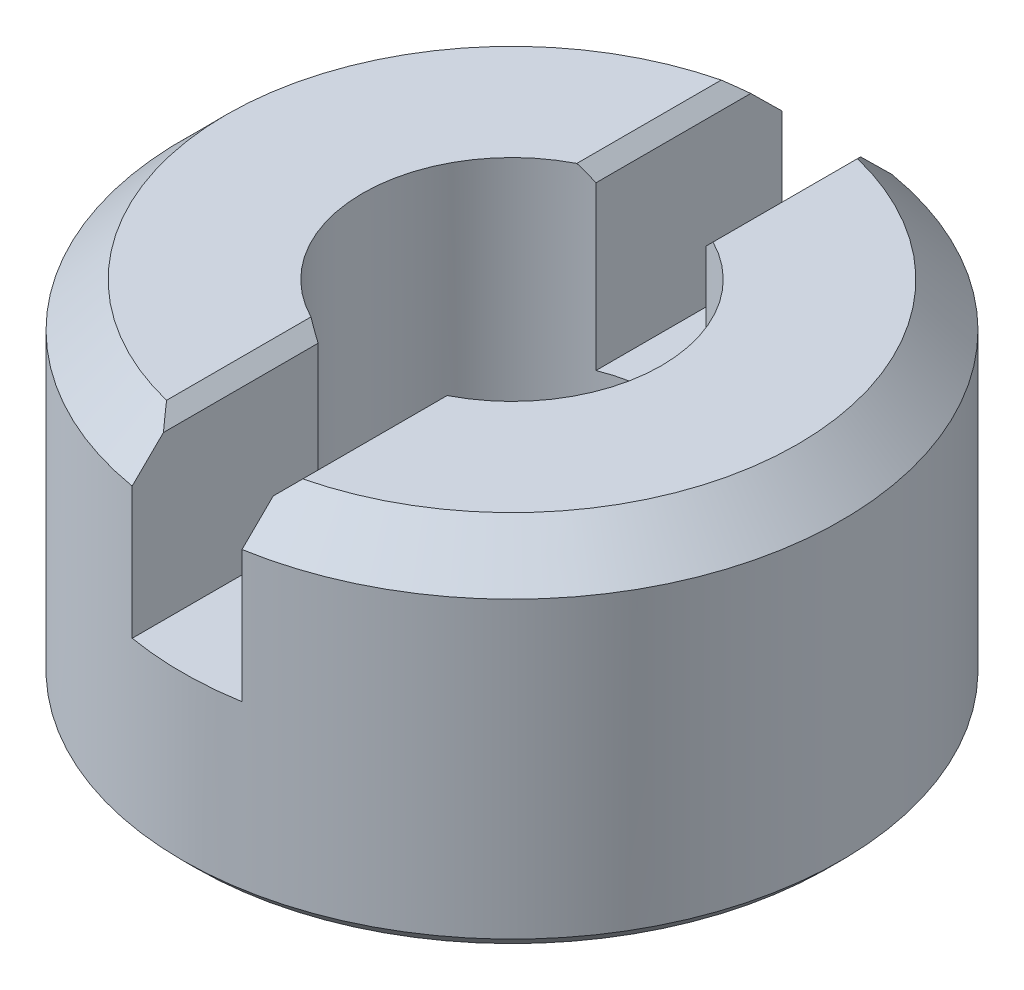
SolidWorks part; units mm, degrees
ref_plane "Přední rovina" through (0, 0, 0) normal (0, 0, 1) x (1, 0, 0)
ref_plane "Vrchní rovina" through (0, 0, 0) normal (0, 1, 0) x (1, 0, 0)
ref_plane "Pravá rovina" through (0, 0, 0) normal (1, 0, 0) x (0, 0, -1)
sketch "Skica1" plane through (0, 0, 0) normal (0, 1, 0) x (1, 0, 0)
  circle A0 centre (0, 0) radius 1.5
  dimension "D1" = 3
extrude "Vysunout1" add sketch "Skica1" along normal blind 1.6
sketch "Skica2" plane through (0, 1.6, 0) normal (0, 1, 0) x (-1, 0, 0)
  line L0 (0, 0) -> (0, 1.5) construction
  line L1 (-0.25, -1.5) -> (0.25, -1.5)
  line L2 (-0.25, -1.5) -> (-0.25, 1.5)
  line L3 (-0.25, 1.5) -> (0.25, 1.5)
  line L4 (0.25, -1.5) -> (0.25, 1.5)
  circle A0 centre (0, 0) radius 1.5 construction
  dimension "n" = 0.5
extrude "Odebrat vysunutím2" cut sketch "Skica2" against normal blind 0.8
chamfer "Zkosit1" distance 0.2 angle 45 2 edges at (1.5, 1.6, 0) (-1.5, 1.6, 0)
chamfer "Zkosit3" distance 0.06 angle 45 5 edges at (0, 0, 1.5) (-0.25, 1.6, 0) (0.25, 1.6, 0)
sketch "Skica3" plane through (0, 0, 0) normal (0, -1, 0) x (1, 0, 0)
  circle A0 centre (0, 0) radius 0.68
  dimension "D1" = 1.36
extrude "Odebrat vysunutím3" cut sketch "Skica3" against normal through all
cosmetic thread "Kosmetický závit1" parameters "M"=1.6
sketch "Skica4" plane through (0, 0, 0) normal (0, 0, 1) x (1, 0, 0)
  line L0 (-0.8, 0) -> (0, 0)
  line L2 (0, 0) -> (0, 0.4619)
  line L3 (0, 0.4619) -> (-0.8, 0)
  line L4 (0, 0) -> (0, 0.8) construction
  line L6 (0.25, 0.8) -> (-0.25, 0.8) construction
  line L7 (-1.5, 0) -> (1.5, 0) construction
  dimension "D1" = 30
  dimension "D2" = 1.6
revolve "Odebrat otočením1" cut sketch "Skica4" angle 360 about L4
equation "\"D1@Zkosit3\" = 0.3 * \"c@Zkosit1\""
equation "\"D1@Skica3\" = \"M@Kosmetický závit1\" * 0.85"
equation "\"D2@Skica4\" = \"M@Kosmetický závit1\""
